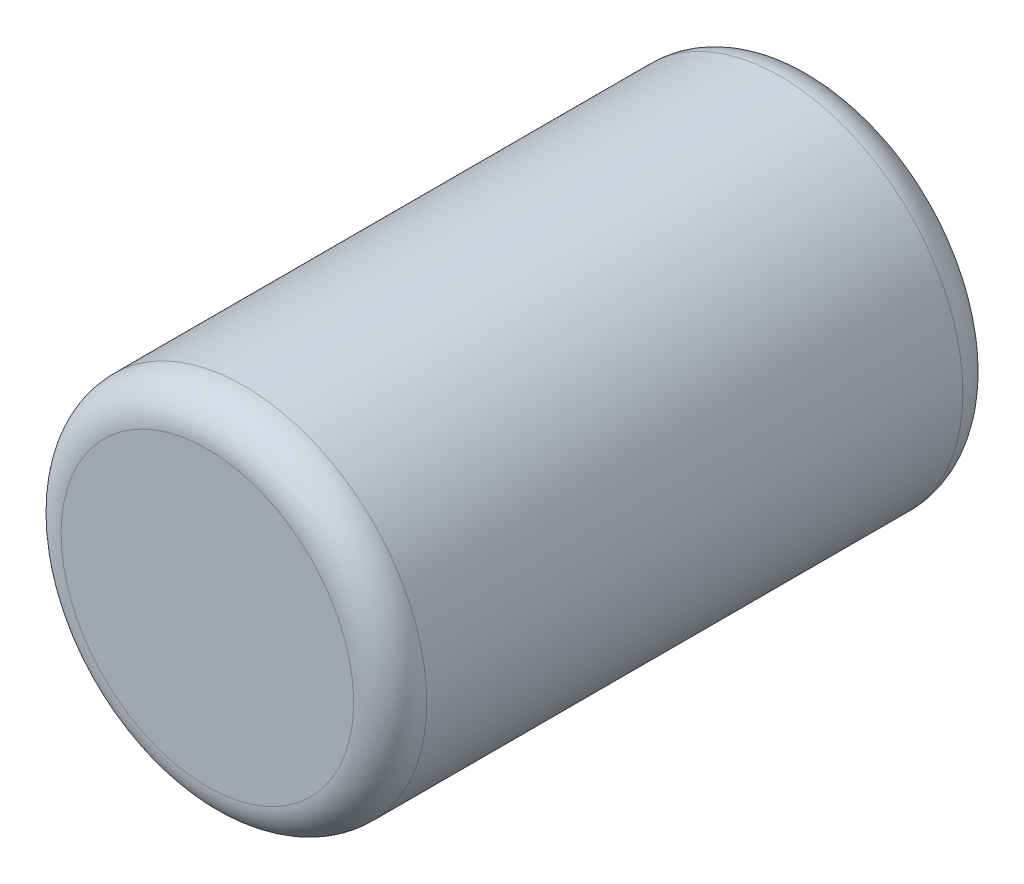
SolidWorks part; units mm, degrees
ref_plane "Front" through (0, 0, 0) normal (0, 0, 1) x (1, 0, 0)
ref_plane "Top" through (0, 0, 0) normal (0, 1, 0) x (1, 0, 0)
ref_plane "Right" through (0, 0, 0) normal (1, 0, 0) x (0, 0, -1)
sketch "Эскиз1" plane through (0, 0, 0) normal (1, 0, 0) x (0, 0, -1)
  line L0 (0, 0) -> (-9.8044, 0) construction
  line L1 (0, 0) -> (-5, 0)
  line L2 (0, 0) -> (0, -1.2)
  line L3 (-0.3, -1.5) -> (-4.7, -1.5)
  line L4 (-5, -1.2) -> (-5, 0)
  arc A0 (0, -1.2) -> (-0.3, -1.5) centre (-0.3, -1.2) cw
  arc A1 (-4.7, -1.5) -> (-5, -1.2) centre (-4.7, -1.2) cw
  dimension "D1" = 3
  dimension "D3" = 0.3
  dimension "D2" = 5
revolve "Повернуть1" add sketch "Эскиз1" angle 360 about L0
